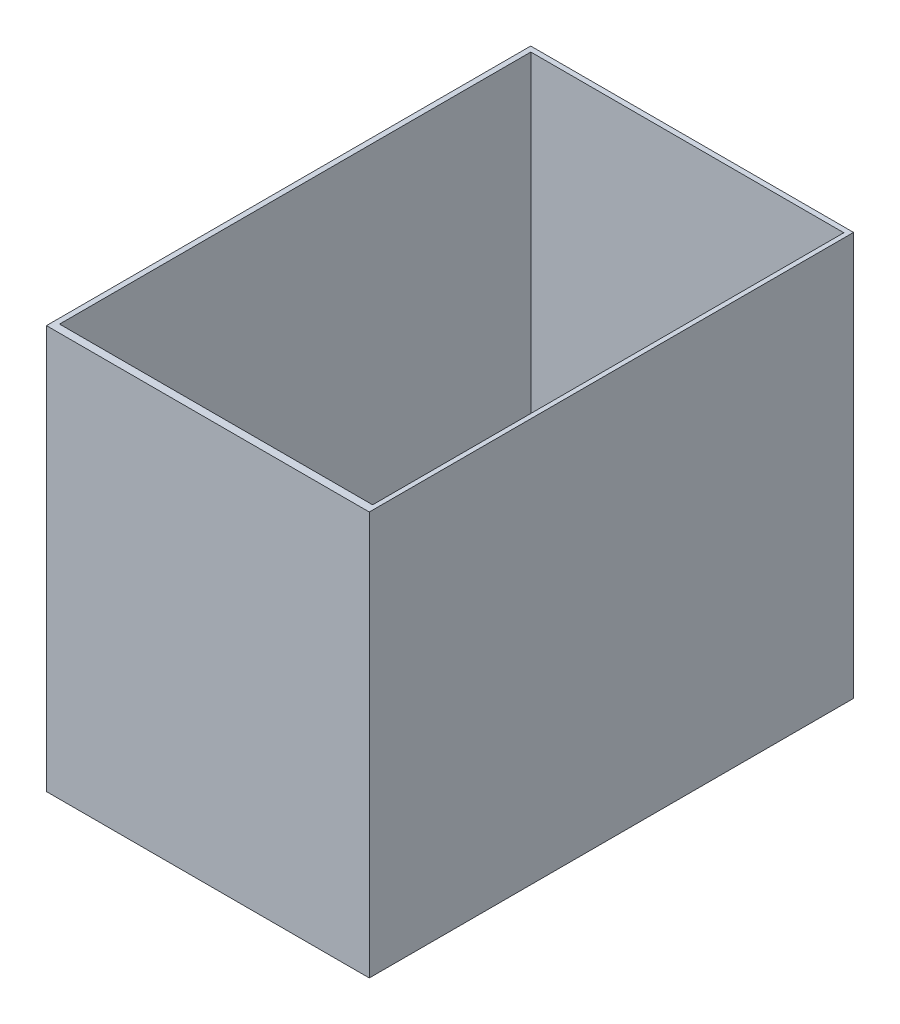
SolidWorks part; units mm, degrees
ref_plane "Front Plane" through (0, 0, 0) normal (0, 0, 1) x (1, 0, 0)
ref_plane "Top Plane" through (0, 0, 0) normal (0, 1, 0) x (1, 0, 0)
ref_plane "Right Plane" through (0, 0, 0) normal (1, 0, 0) x (0, 0, -1)
sketch "Sketch1" plane through (0, 0, 0) normal (0, 1, 0) x (1, 0, 0)
  line L1 (-342.2047, 193.0551) -> (457.7953, 193.0551)
  line L2 (-342.2047, 193.0551) -> (-342.2047, -1006.9449)
  line L3 (-342.2047, -1006.9449) -> (457.7953, -1006.9449)
  line L4 (457.7953, 193.0551) -> (457.7953, -1006.9449)
  dimension "D1" = 800
  dimension "D2" = 1200
extrude "Boss-Extrude1" add sketch "Sketch1" along normal blind 1000
sketch "Sketch2" plane through (0, 1000, 0) normal (0, 1, 0) x (1, 0, 0)
  line L1 (-329.1886, 180.2683) -> (446.5025, 180.2683)
  line L2 (-329.1886, 180.2683) -> (-329.1886, -987.4567)
  line L3 (-329.1886, -987.4567) -> (446.5025, -987.4567)
  line L4 (446.5025, 180.2683) -> (446.5025, -987.4567)
extrude "Cut-Extrude1" cut sketch "Sketch2" against normal blind 900
